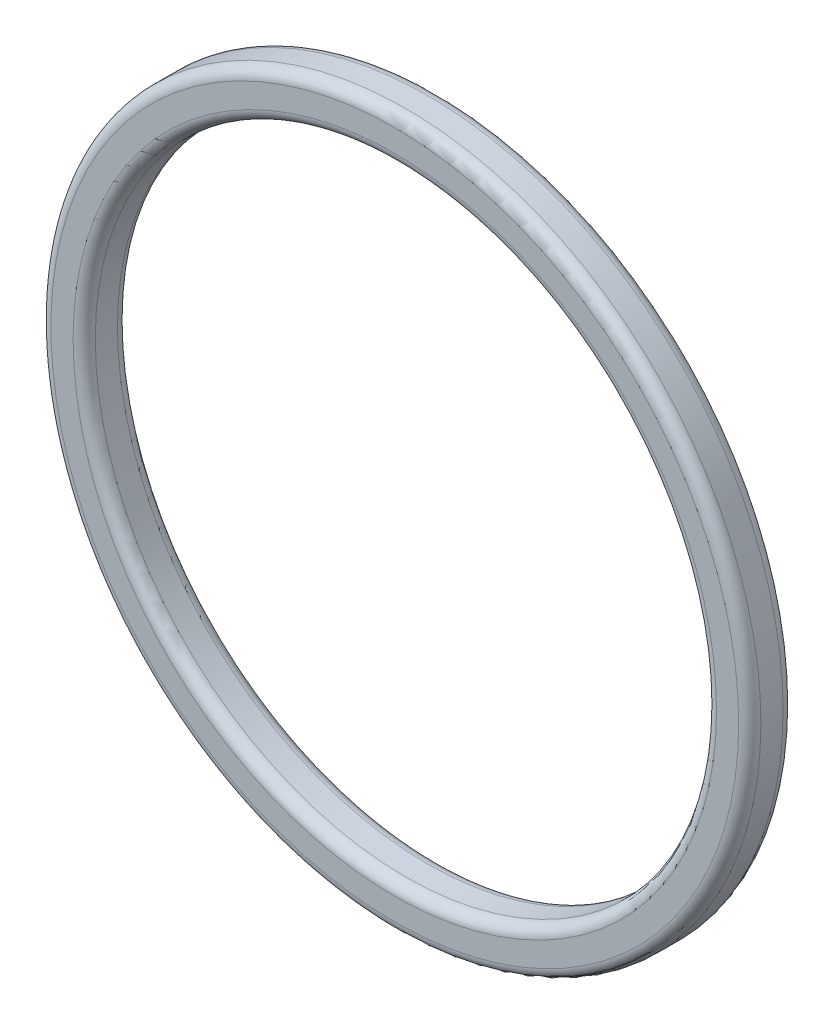
SolidWorks part; units mm, degrees
ref_plane "Front Plane" through (0, 0, 0) normal (0, 0, 1) x (1, 0, 0)
ref_plane "Top Plane" through (0, 0, 0) normal (0, 1, 0) x (1, 0, 0)
ref_plane "Right Plane" through (0, 0, 0) normal (1, 0, 0) x (0, 0, -1)
sketch "Sketch1" plane through (0, 0, 0) normal (0, 0, 1) x (1, 0, 0)
  circle A0 centre (0, 0) radius 7
  circle A1 centre (0, 0) radius 8
  dimension "D1" = 14
  dimension "D2" = 16
extrude "Boss-Extrude1" add sketch "Sketch1" along normal blind 1
fillet "Fillet1" radius 0.25 1 edges at (8, 0, 1)
fillet "Fillet2" radius 0.25 1 edges at (7, 0, 1)
fillet "Fillet3" radius 0.25 1 edges at (8, 0, 0)
fillet "Fillet4" radius 0.25 1 edges at (7, 0, 0)
